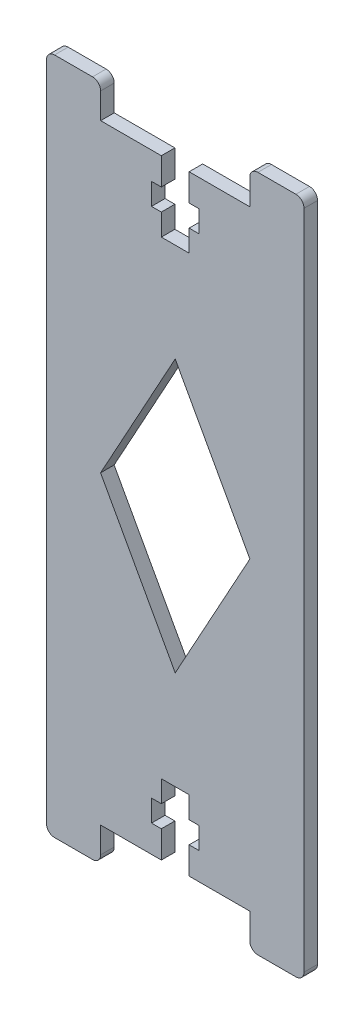
SolidWorks part; units mm, degrees
ref_plane "前视基准面" through (0, 0, 0) normal (0, 0, 1) x (1, 0, 0)
ref_plane "上视基准面" through (0, 0, 0) normal (0, 1, 0) x (1, 0, 0)
ref_plane "右视基准面" through (0, 0, 0) normal (1, 0, 0) x (0, 0, -1)
sketch "草图1" plane through (0, 0, 0) normal (0, 0, 1) x (1, 0, 0)
  line L0 (-3.9409, 0) -> (-3.9409, 19.9) construction
  line L1 (15.0591, 15.4) -> (15.0591, -84.6)
  line L2 (15.0591, -34.6) -> (-22.9409, -34.6) construction
  line L3 (-3.9409, -69.2) -> (-3.9409, -89.1) construction
  line L4 (7.0591, -84.6) -> (15.0591, -84.6)
  line L5 (7.0591, -79.6) -> (7.0591, -84.6)
  line L6 (-5.9909, 0) -> (-1.8909, 0)
  line L7 (-1.8909, 0) -> (-1.8909, 3.2)
  line L8 (-1.8909, 3.2) -> (-0.4409, 3.2)
  line L9 (-0.4409, 3.2) -> (-0.4409, 6.4)
  line L10 (-0.4409, 6.4) -> (-1.8909, 6.4)
  line L11 (-1.8909, 6.4) -> (-1.8909, 10.4)
  line L12 (-1.8909, 10.4) -> (7.0591, 10.4)
  line L13 (7.0591, 10.4) -> (7.0591, 15.4)
  line L14 (7.0591, 15.4) -> (15.0591, 15.4)
  line L15 (-1.8909, -79.6) -> (7.0591, -79.6)
  line L16 (-1.8909, -75.6) -> (-1.8909, -79.6)
  line L17 (-0.4409, -75.6) -> (-1.8909, -75.6)
  line L18 (-0.4409, -72.4) -> (-0.4409, -75.6)
  line L19 (-1.8909, -72.4) -> (-0.4409, -72.4)
  line L20 (-1.8909, -69.2) -> (-1.8909, -72.4)
  line L21 (-5.9909, -69.2) -> (-1.8909, -69.2)
  line L22 (-5.9909, -69.2) -> (-5.9909, -72.4)
  line L23 (-5.9909, -72.4) -> (-7.4409, -72.4)
  line L24 (-7.4409, -72.4) -> (-7.4409, -75.6)
  line L25 (-7.4409, -75.6) -> (-5.9909, -75.6)
  line L26 (-5.9909, -75.6) -> (-5.9909, -79.6)
  line L27 (-5.9909, -79.6) -> (-14.9409, -79.6)
  line L28 (-14.9409, 15.4) -> (-22.9409, 15.4)
  line L29 (-14.9409, 10.4) -> (-14.9409, 15.4)
  line L30 (-5.9909, 10.4) -> (-14.9409, 10.4)
  line L31 (-5.9909, 6.4) -> (-5.9909, 10.4)
  line L32 (-7.4409, 6.4) -> (-5.9909, 6.4)
  line L33 (-7.4409, 3.2) -> (-7.4409, 6.4)
  line L34 (-5.9909, 3.2) -> (-7.4409, 3.2)
  line L35 (-5.9909, 0) -> (-5.9909, 3.2)
  line L36 (-14.9409, -79.6) -> (-14.9409, -84.6)
  line L37 (-14.9409, -84.6) -> (-22.9409, -84.6)
  line L38 (-22.9409, 15.4) -> (-22.9409, -84.6)
  line L39 (-3.9409, 0) -> (-22.9409, -34.6) construction
  line L40 (-22.9409, -34.6) -> (-3.9409, -69.2) construction
  line L41 (-3.9409, -69.2) -> (15.0591, -34.6) construction
  line L42 (15.0591, -34.6) -> (-3.9409, 0) construction
  line L43 (-3.9409, -14.5429) -> (-14.9549, -34.6)
  line L44 (-14.9549, -34.6) -> (-3.9409, -54.6571)
  line L45 (-3.9409, -54.6571) -> (7.0731, -34.6)
  line L46 (7.0731, -34.6) -> (-3.9409, -14.5429)
  line L47 (11.0591, 15.4) -> (11.0591, 9.7) construction
  point P26 (-3.9409, -34.6)
  point P50 (-0.4409, 4.8)
  dimension "D1" = 2.05
  dimension "D2" = 3.2
  dimension "D3" = 7
  dimension "D4" = 3.2
  dimension "D5" = 4
  dimension "D6" = 15
  dimension "D7" = 5
  dimension "D8" = 8
  dimension "D9" = 90
  dimension "D10" = 7
extrude "凸台-拉伸1" add sketch "草图1" along normal blind 2
fillet "圆角1" radius 1.2 8 edges at (-22.9409, 15.4, 1) (-14.9409, 15.4, 1) (7.0591, 15.4, 1) (15.0591, 15.4, 1) (-22.9409, -84.6, 1) (-14.9409, -84.6, 1) (7.0591, -84.6, 1) (15.0591, -84.6, 1)
sketch "草图2" plane through (0, 10.4, 0) normal (0, 1, 0) x (1, 0, 0)
  line L0 (-5.9909, -1) -> (-1.8909, -1)
  line L1 (-5.9909, -2) -> (-5.9909, 0) construction
  line L2 (-1.8909, -2) -> (-1.8909, 0) construction
  circle A0 centre (-3.9409, -1) radius 2.05
sketch "草图3" plane through (0, -79.6, 0) normal (0, -1, 0) x (1, 0, 0)
  line L0 (-5.9909, 1) -> (-1.8909, 1)
  line L1 (-5.9909, 2) -> (-5.9909, 0) construction
  line L2 (-1.8909, 2) -> (-1.8909, 0) construction
  circle A0 centre (-3.9409, 1) radius 2.05
